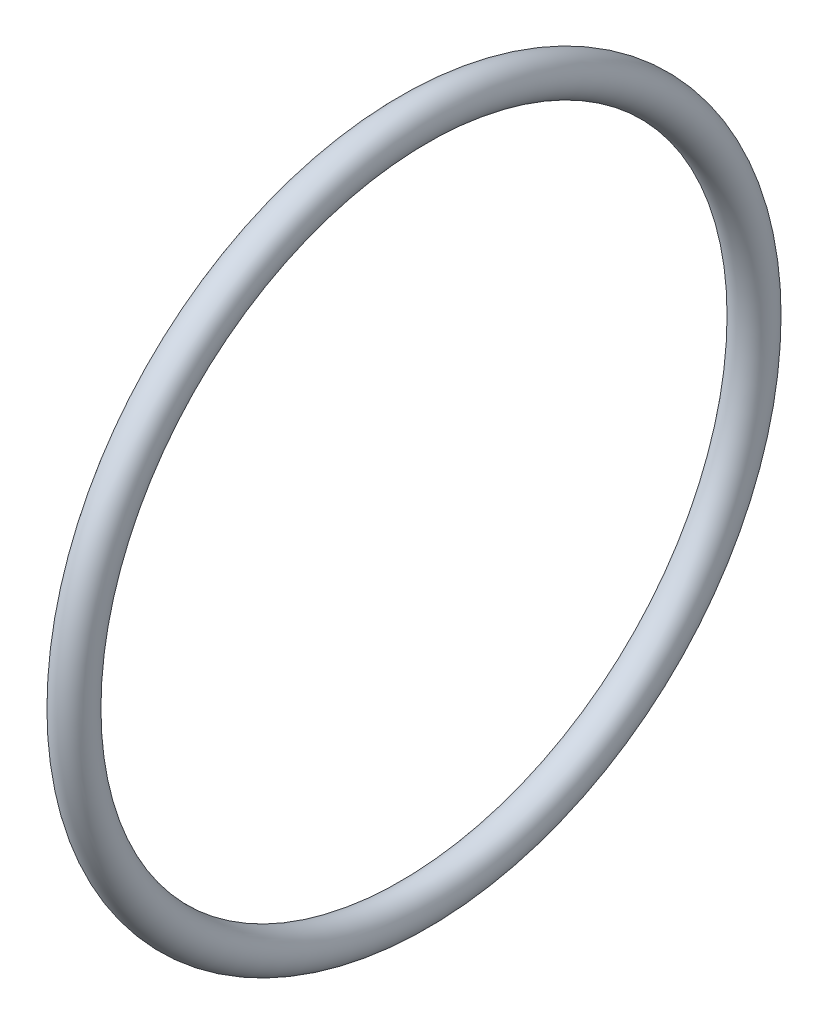
SolidWorks part; units mm, degrees
ref_plane "Front Plane" through (0, 0, 0) normal (0, 0, 1) x (1, 0, 0)
ref_plane "Top Plane" through (0, 0, 0) normal (0, 1, 0) x (1, 0, 0)
ref_plane "Right Plane" through (0, 0, 0) normal (1, 0, 0) x (0, 0, -1)
sketch "Sketch1" plane through (0, 0, 0) normal (1, 0, 0) x (0, 0, -1)
  circle A0 centre (0, 0) radius 25.4 construction
  dimension "D1" = 50.8
sketch "Sketch2" plane through (0, 0, 0) normal (0, 0, 1) x (1, 0, 0)
  line L0 (0, 0) -> (0, 26.67) construction
  line L1 (0, 28.2575) -> (0, 26.67) construction
  circle A0 centre (0, 28.2575) radius 1.5875
  point P5 (0, 0)
  dimension "D2" = 3.175
  dimension "D1" = 26.67
sketch "Sketch4" plane through (0, 0, 0) normal (0, 1, 0) x (1, 0, 0)
  line L0 (0, 0) -> (7.9232, 0) construction
revolve "Revolve1" add sketch "Sketch2" angle 360 about L0
